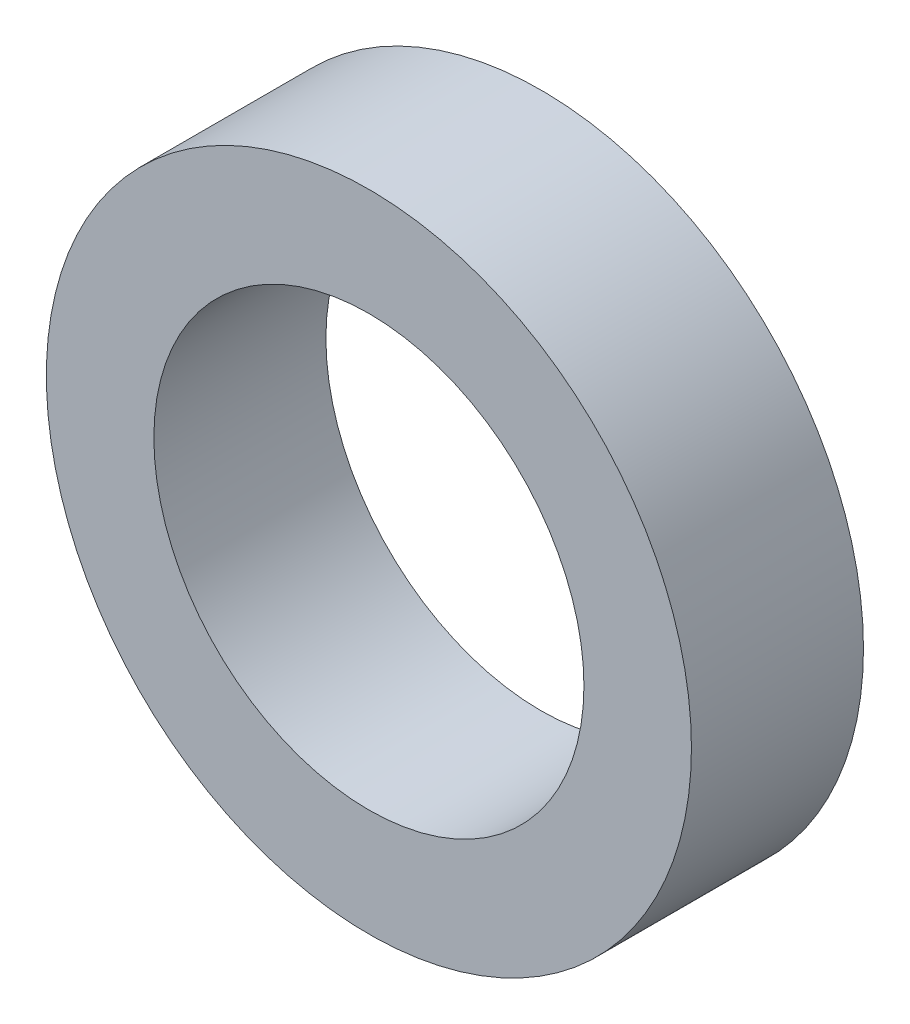
SolidWorks part; units mm, degrees
ref_plane "Plan de face" through (0, 0, 0) normal (0, 0, 1) x (1, 0, 0)
ref_plane "Plan de dessus" through (0, 0, 0) normal (0, 1, 0) x (1, 0, 0)
ref_plane "Plan de droite" through (0, 0, 0) normal (1, 0, 0) x (0, 0, -1)
sketch "Esquisse1" plane through (0, 0, 0) normal (0, 0, 1) x (1, 0, 0)
  circle A0 centre (0, 0) radius 5
  circle A1 centre (0, 0) radius 7.5
  dimension "D1" = 10
  dimension "D2" = 15
extrude "Boss.-Extru.1" add sketch "Esquisse1" along normal mid plane 4
